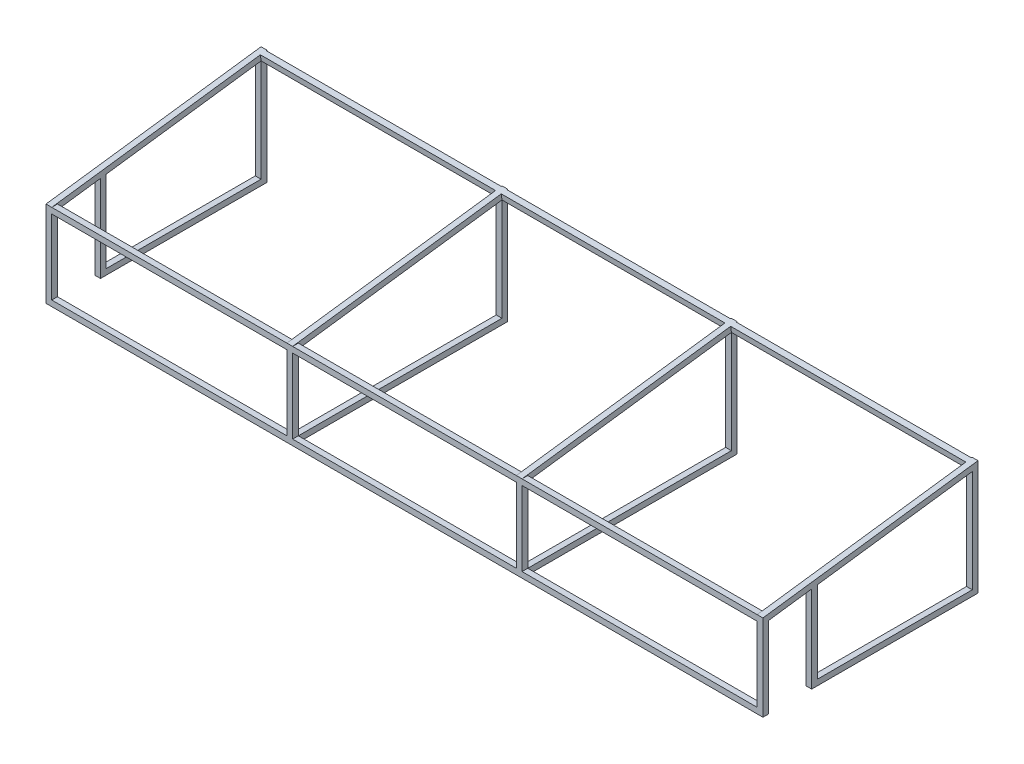
SolidWorks part; units mm, degrees
ref_plane "Front Plane" through (0, 0, 0) normal (0, 0, 1) x (1, 0, 0)
ref_plane "Top Plane" through (0, 0, 0) normal (0, 1, 0) x (1, 0, 0)
ref_plane "Right Plane" through (0, 0, 0) normal (1, 0, 0) x (0, 0, -1)
sketch "Sketch2" plane through (0, 0, 0) normal (1, 0, 0) x (0, 0, -1)
  line L0 (-2.6433, -0.3524) -> (-750, -100)
  line L1 (-750, -100) -> (-750, -400)
  line L2 (-750, -400) -> (-730, -400)
  line L3 (-730, -400) -> (-730, -117.5103)
  line L4 (-730, -117.5103) -> (0, -20.177)
  line L5 (0, -20.177) -> (0, 0) construction
  line L6 (0, -20.177) -> (-2.6433, -0.3524) construction
  line L7 (0, -20.177) -> (0, 0)
  line L8 (0, 0) -> (-2.6433, -0.3524)
  dimension "D1" = 20
  dimension "D2" = 20
  dimension "D3" = 750
  dimension "D4" = 300
  dimension "D5" = 100
extrude "Boss-Extrude2" add sketch "Sketch2" against normal blind 20 from offset 1250
sketch "Sketch3" plane through (0, 0, 0) normal (1, 0, 0) x (0, 0, -1)
  line L0 (-730, -117.5103) -> (0, -20.177) construction
  line L2 (0, -20.177) -> (-2.6433, -0.3524)
  line L3 (0, 0) -> (-750, -100) construction
  line L4 (-2.6433, -0.3524) -> (-22.4678, -2.9957)
  line L5 (-22.4678, -2.9957) -> (-19.8246, -22.8203)
  line L6 (-19.8246, -22.8203) -> (0, -20.177)
  line L7 (-730, -400) -> (-730, -117.5103) construction
  line L8 (-750, -400) -> (-730, -400)
  line L9 (-750, -400) -> (-750, -380)
  line L10 (-750, -380) -> (-730, -380)
  line L11 (-730, -400) -> (-730, -380)
  line L12 (0, -20.177) -> (0, 0) construction
  line L13 (-750, -100) -> (-730, -100)
  line L14 (-750, -100) -> (-750, -120)
  line L15 (-750, -120) -> (-730, -120)
  line L16 (-730, -100) -> (-730, -120)
  dimension "D1" = 20
extrude "Boss-Extrude3" add sketch "Sketch3" along normal mid plane 2500
sketch "Sketch4" [suppressed] plane through (1250, 0, 0) normal (1, 0, 0) x (0, 0, -1)
  line L0 (-2.6433, -0.3524) -> (0.3833, -0.3524)
  line L1 (0.3833, -0.3524) -> (3, -19.9779)
  line L2 (3, -19.9779) -> (3, -54.9779)
  line L4 (3, -54.9779) -> (0, -54.9779)
  line L5 (0, -54.9779) -> (0, -20.177)
  line L6 (0, -20.177) -> (-2.6433, -0.3524)
  dimension "D1" = 3
  dimension "D2" = 3
  dimension "D3" = 35
pattern_linear "LPattern1" count 2 spacing 840 along (-1, 0, 0) of "Boss-Extrude2"
mirror "Mirror1" about plane through (0, 0, 0) normal (1, 0, 0) of "LPattern1", "Boss-Extrude2"
sketch "Sketch6" plane through (0, 0, 730) normal (0, 0, -1) x (-1, 0, 0)
  line L0 (1250, -400) -> (-1250, -400) construction
  line L1 (-410, -380) -> (-390, -380)
  line L2 (-410, -380) -> (-410, -400)
  line L3 (-410, -400) -> (-390, -400)
  line L4 (-390, -380) -> (-390, -400)
  line L6 (390, -380) -> (410, -380)
  line L7 (390, -380) -> (390, -400)
  line L8 (390, -400) -> (410, -400)
  line L9 (410, -380) -> (410, -400)
  line L10 (-1230, -380) -> (-1250, -380)
  line L11 (-1230, -380) -> (-1230, -400)
  line L12 (-1230, -400) -> (-1250, -400)
  line L13 (-1250, -380) -> (-1250, -400)
  line L14 (1230, -380) -> (1250, -380)
  line L15 (1230, -380) -> (1230, -400)
  line L16 (1230, -400) -> (1250, -400)
  line L17 (1250, -380) -> (1250, -400)
extrude "Boss-Extrude7" add sketch "Sketch6" along normal through all
sketch "Sketch7" plane through (0, 0, 0) normal (0, 0, -1) x (-1, 0, 0)
  line L1 (-1250, -400) -> (-1230, -400)
  line L2 (-1250, -400) -> (-1250, -20.177)
  line L3 (-1250, -20.177) -> (-1230, -20.177)
  line L4 (-1230, -400) -> (-1230, -20.177)
  line L5 (-410, -400) -> (-390, -400)
  line L6 (-410, -400) -> (-410, -20.177)
  line L7 (-410, -20.177) -> (-390, -20.177)
  line L8 (-390, -400) -> (-390, -20.177)
  line L9 (390, -400) -> (410, -400)
  line L10 (390, -400) -> (390, -20.177)
  line L11 (390, -20.177) -> (410, -20.177)
  line L12 (410, -400) -> (410, -20.177)
  line L13 (1230, -400) -> (1250, -400)
  line L14 (1230, -400) -> (1230, -20.177)
  line L15 (1230, -20.177) -> (1250, -20.177)
  line L16 (1250, -400) -> (1250, -20.177)
extrude "Boss-Extrude8" add sketch "Sketch7" against normal blind 20
sketch "Sketch8" plane through (1250, 0, 0) normal (1, 0, 0) x (0, 0, -1)
  line L0 (-730, -400) -> (-730, -117.5103)
  line L1 (-730, -117.5103) -> (-20, -22.8437)
  line L2 (-20, -22.8437) -> (0, -20.177)
  line L3 (0, -20.177) -> (0, -400)
  line L4 (0, -400) -> (-730, -400)
extrude "Cut-Extrude1" [suppressed] cut sketch "Sketch8" against normal blind 20
sketch "Sketch9" plane through (-1250, 0, 0) normal (-1, 0, 0) x (0, 0, 1)
  line L0 (0, -400) -> (730, -400)
  line L1 (730, -400) -> (730, -117.5103)
  line L2 (730, -117.5103) -> (20, -22.8437)
  line L3 (20, -22.8437) -> (0, -20.177)
  line L4 (0, -20.177) -> (0, -400)
extrude "Cut-Extrude2" cut sketch "Sketch9" against normal blind 20
sketch "Sketch10" plane through (1250, 0, 0) normal (1, 0, 0) x (0, 0, -1)
  line L0 (-750, -400) -> (0, -400) construction
  line L1 (-580, -400) -> (-560, -400)
  line L2 (-580, -400) -> (-580, -94.8437)
  line L3 (-580, -94.8437) -> (-560, -94.8437)
  line L4 (-560, -400) -> (-560, -94.8437)
  line L5 (-730, -117.5103) -> (-20, -22.8437) construction
  line L6 (-730, -380) -> (-730, -117.5103) construction
  dimension "D1" = 20
  dimension "D2" = 150
extrude "Boss-Extrude9" add sketch "Sketch10" against normal blind 20
sketch "Sketch11" plane through (1250, 0, 0) normal (1, 0, 0) x (0, 0, -1)
  line L0 (-750, -400) -> (0, -400) construction
  line L1 (-730, -380) -> (-580, -380)
  line L2 (-730, -380) -> (-730, -400)
  line L3 (-730, -400) -> (-580, -400)
  line L4 (-580, -380) -> (-580, -400)
extrude "Cut-Extrude3" cut sketch "Sketch11" against normal blind 20
sketch "Sketch12" plane through (-1250, 0, 0) normal (-1, 0, 0) x (0, 0, 1)
  line L0 (0, -400) -> (730, -400) construction
  line L1 (0, -20.177) -> (20, -20.177)
  line L2 (0, -20.177) -> (0, -400)
  line L4 (20, -20.177) -> (20, -380)
  line L6 (0, -400) -> (580, -400)
  line L8 (20, -380) -> (560, -380)
  line L10 (560, -94.8437) -> (580, -94.8437)
  line L11 (560, -94.8437) -> (560, -380)
  line L13 (580, -94.8437) -> (580, -400)
extrude "Boss-Extrude10" add sketch "Sketch12" against normal blind 20
